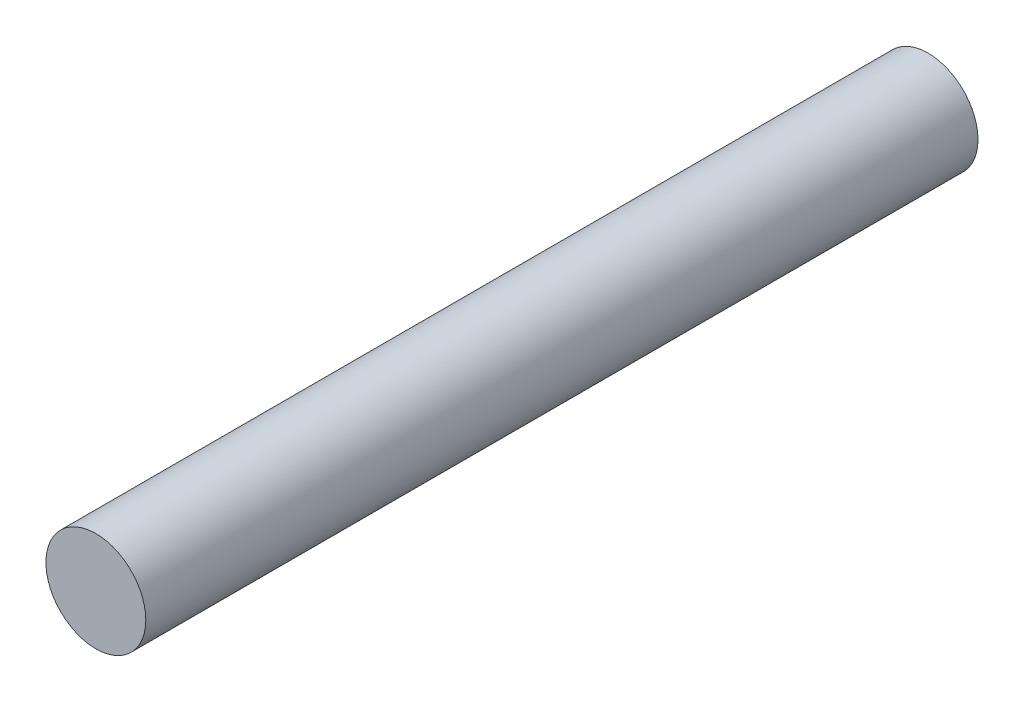
SolidWorks part; units mm, degrees
material "1.6566 (17NiCrMo6-4)"
ref_plane "前视基准面" through (0, 0, 0) normal (0, 0, 1) x (1, 0, 0)
ref_plane "上视基准面" through (0, 0, 0) normal (0, 1, 0) x (1, 0, 0)
ref_plane "右视基准面" through (0, 0, 0) normal (1, 0, 0) x (0, 0, -1)
sketch "草图1" plane through (0, 0, 0) normal (0, 0, 1) x (1, 0, 0)
  circle A0 centre (0, 0) radius 1.5
extrude "凸台-拉伸1" add sketch "草图1" along normal blind 25
